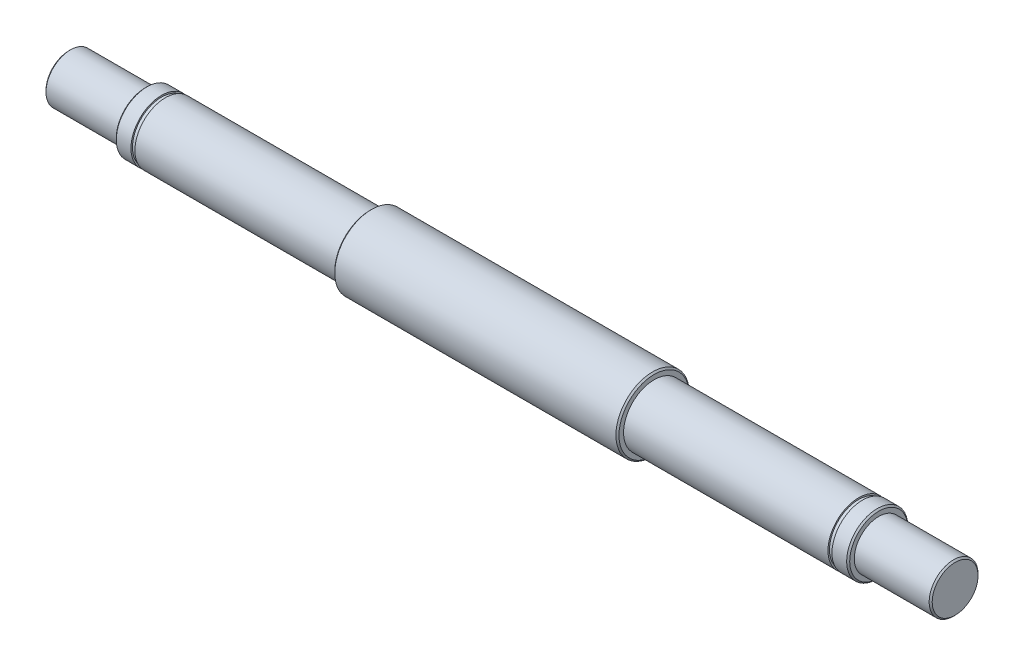
SolidWorks part; units mm, degrees
ref_plane "Front Plane" through (0, 0, 0) normal (0, 0, 1) x (1, 0, 0)
ref_plane "Top Plane" through (0, 0, 0) normal (0, 1, 0) x (1, 0, 0)
ref_plane "Right Plane" through (0, 0, 0) normal (1, 0, 0) x (0, 0, -1)
sketch "Sketch1" plane through (0, 0, 0) normal (0, 1, 0) x (1, 0, 0)
  line L0 (-145, 0) -> (145, 0) construction
  line L1 (-145, 0) -> (-145, 8)
  line L2 (-145, 8) -> (-120, 8)
  line L3 (-120, 8) -> (-120, 10)
  line L4 (0, 0) -> (0, 68.7304) construction
  line L5 (-120, 10) -> (-114.7, 10)
  line L6 (-46.5, 10) -> (-46.5, 12)
  line L7 (-46.5, 12) -> (46.5, 12)
  line L8 (-113.5, 12.5) -> (-113.5, -12.5) construction
  line L9 (-114.7, 10) -> (-114.7, 9.5)
  line L10 (-114.7, 9.5) -> (-113.4, 9.5)
  line L11 (-113.4, 9.5) -> (-113.4, 10)
  line L12 (-113.4, 10) -> (-46.5, 10)
  line L13 (113.4, 10) -> (46.5, 10)
  line L14 (113.4, 9.5) -> (113.4, 10)
  line L15 (114.7, 9.5) -> (113.4, 9.5)
  line L16 (114.7, 10) -> (114.7, 9.5)
  line L17 (46.5, 10) -> (46.5, 12)
  line L18 (120, 10) -> (114.7, 10)
  line L19 (120, 8) -> (120, 10)
  line L20 (145, 8) -> (120, 8)
  line L21 (145, 0) -> (145, 8)
  line L22 (-145, 0) -> (145, 0)
  line L23 (-58.5, -17) -> (-58.5, 17) construction
  point P19 (0, 12)
  dimension "D1" = 290
  dimension "D2" = 24
  dimension "D3" = 20
  dimension "D4" = 16
  dimension "D5" = 25
  dimension "D7" = 19
  dimension "D8" = 1.3
  dimension "D9" = 0.1
  dimension "D6" = 12
revolve "Revolve1" add sketch "Sketch1" angle 360 about L22
chamfer "Chamfer1" distance 0.5 angle 45 6 edges at (120, 0, 10) (145, 0, 8) (46.5, 0, 12) (-46.5, 0, 12) (-120, 0, 10) (-145, 0, 8)
equation "\"d_ext_rouleau\"= 120"
equation "\"epaisseur_rouleau\"=80"
equation "\"alesage-rouleau\"= 52"
equation "\"jeu_dent_rouleau\"= 2"
equation "\"profondeur_dent_rouleau\"=4"
equation "\"n_dent_roueau\"= 15"
equation "\"B_roulement_rouleau\"= 12"
equation "\"F_anneau_alesage_rouleau\"=1.85"
equation "\"G_anneau_alesage_rouleau\"=47.5"
equation "\"K_anneau_alesage_rouleau\"=3.75"
equation "\"d_vis_flasque_rouleau\"=5"
equation "\"h_matrice\"= 15"
equation "\"d_matrice\"= 250"
equation "\"d_granulat\"= 8"
equation "\"zone_vide_matrice\" = 70"
equation "\"d_alesage_matrice\"=50"
equation "\"a_clavette_alesage_matrice\"=16"
equation "\"D2@Sketch1\"=\"d_int_roulement_rouleau\" + 4"
equation "\"D1@Sketch1\"=\"d_matrice\"+40"
equation "\"g_anneau_arbre_rouleau\"=19"
equation "\"D7@Sketch1\"=\"g_anneau_arbre_rouleau\""
equation "\"f_anneau_arbre_rouleau\"=1.3"
equation "\"D8@Sketch1\"=\"f_anneau_arbre_rouleau\""
equation "\"k_anneau_arbre_rouleau\"=1.5"
equation "\"d_ext_roulement_rouleau\"= 42"
equation "\"d_int_roulement_rouleau\"= 20"
